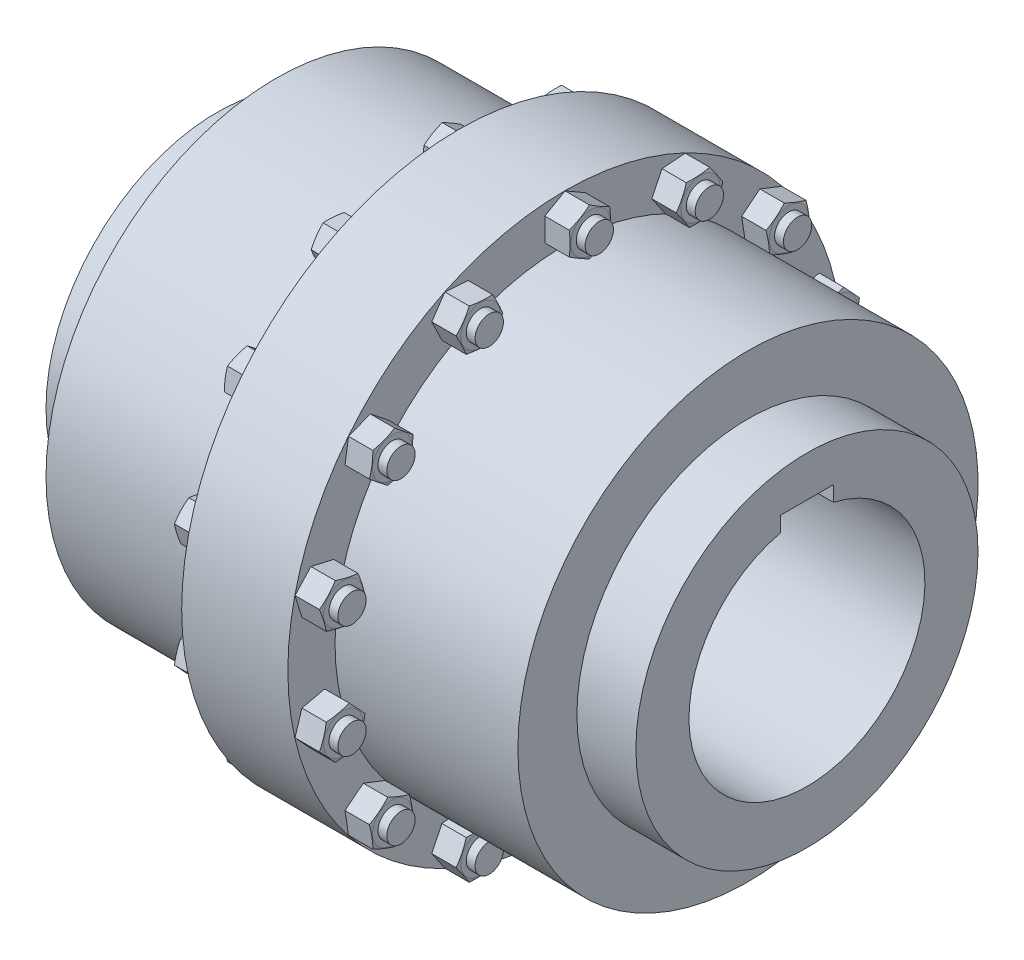
SolidWorks part; units mm, degrees
ref_plane "Спереди" through (0, 0, 0) normal (0, 0, 1) x (1, 0, 0)
ref_plane "Сверху" through (0, 0, 0) normal (0, 1, 0) x (1, 0, 0)
ref_plane "Справа" through (0, 0, 0) normal (1, 0, 0) x (0, 0, -1)
sketch "Эскиз1" plane through (0, 0, 0) normal (0, 0, 1) x (1, 0, 0)
  line L0 (-250, 100) -> (-250, 145)
  line L1 (-250, 145) -> (-200, 145)
  line L2 (-200, 145) -> (-200, 195)
  line L3 (-200, 195) -> (-45, 195)
  line L4 (200, 195) -> (200, 145)
  line L5 (45, 235) -> (45, 195)
  line L6 (45, 235) -> (-45, 235)
  line L7 (-45, 235) -> (-45, 195)
  line L8 (45, 195) -> (200, 195)
  line L9 (200, 145) -> (250, 145)
  line L10 (250, 145) -> (250, 100)
  line L12 (-10, 145) -> (-10, 100)
  line L15 (10, 145) -> (10, 100)
  line L16 (-250, 100) -> (-10, 100)
  line L18 (-98.6071, 0) -> (92.8961, 0) construction
  line L25 (10, 100) -> (250, 100)
  line L31 (0, 235) -> (0, -98.3961) construction
  line L34 (-10, 145) -> (-105, 145)
  line L35 (-105, 145) -> (-105, 172.5)
  line L36 (-105, 172.5) -> (105, 172.5)
  line L37 (105, 172.5) -> (105, 145)
  line L38 (-10, 100) -> (0, 100) construction
  line L39 (0, 100) -> (10, 100) construction
  line L40 (105, 145) -> (10, 145)
  line L41 (-199, 172.5) -> (-199, 145)
  line L42 (-199, 145) -> (-145, 145)
  line L45 (145, 172.5) -> (199, 172.5)
  line L46 (199, 172.5) -> (199, 145)
  line L47 (199, 145) -> (145, 145)
  line L48 (145, 145) -> (145, 172.5)
  line L49 (-199, 172.5) -> (-145, 172.5)
  line L50 (-199, 172.5) -> (-200, 172.5) construction
  line L51 (105, 172.5) -> (145, 172.5) construction
  line L52 (199, 172.5) -> (200, 172.5) construction
  line L53 (-145, 172.5) -> (-145, 145)
  line L54 (-105, 172.5) -> (-145, 172.5) construction
  line L55 (-199, 172.5) -> (-199, 195) construction
  line L56 (199, 195) -> (199, 172.5) construction
  point P27 (-125, 172.5)
  point P32 (125, 172.5)
  dimension "D" = 470
  dimension "dmin" = 200
  dimension "D2" = 290
  dimension "D1" = 390
  dimension "lmin" = 240
  dimension "B" = 90
  dimension "L" = 500
  dimension "bmin" = 40
  dimension "A" = 250
  dimension "lminPol" = 400
  dimension "TolKr" = 1
  dimension "TM" = 22.5
revolve "Повернуть1" add sketch "Эскиз1" angle 360 about L18
sketch "Эскиз3" plane through (0, 0, 0) normal (1, 0, 0) x (0, 0, -1)
  line L1 (-22.5, 0) -> (22.5, 0)
  line L2 (-22.5, 0) -> (-22.5, 110.4)
  line L3 (-22.5, 110.4) -> (22.5, 110.4)
  line L4 (22.5, 0) -> (22.5, 110.4)
  point P4 (0, 0)
  dimension "Bshpon" = 45
  dimension "Dplust2shpon" = 110.4
extrude "Вырез-Вытянуть1" cut sketch "Эскиз3" against normal through all both and the other way through all
sketch "Эскиз2" plane through (0, 0, 0) normal (0, 0, 1) x (1, 0, 0)
  line L0 (-60, 215) -> (74, 215)
  line L1 (66.5, 227) -> (66.5, 231.6)
  line L2 (65.6426, 234.8) -> (45, 234.8)
  line L3 (45, -235) -> (45, 235) construction
  line L4 (45, 234.8) -> (45, 227)
  line L6 (-45, 235) -> (-45, -235) construction
  line L7 (-60, 229.4) -> (-60, 215)
  line L8 (-45, 232.9) -> (-45, 227)
  line L9 (-45, 227) -> (45, 227)
  line L10 (-60, 215) -> (48.3147, 215) construction
  line L11 (-59.0622, 232.9) -> (-45, 232.9)
  line L12 (66.5, 227) -> (74, 227)
  line L13 (74, 227) -> (74, 215)
  line L15 (0, 0) -> (45.6917, 0) construction
  line L16 (-59.0622, 232.9) -> (-60, 229.4)
  line L17 (65.6426, 234.8) -> (66.5, 231.6)
  point P17 (-45, 229.95)
  dimension "d1minB" = 24
  dimension "eminG" = 39.6
  dimension "eminB" = 35.8
  dimension "lminB" = 119
  dimension "DB" = 430
  dimension "kminB" = 15
  dimension "mminG" = 21.5
  dimension "D4" = 15
  dimension "D5" = 15
  dimension "Dbolt" = 28.8
  dimension "DG" = 33.2
revolve "Повернуть2" add sketch "Эскиз2" angle 360 about L0
sketch "Эскиз5" plane through (-60, 0, 0) normal (-1, 0, 0) x (0, 0, 1)
  line L1 (0, 197.1) -> (15.5019, 206.05)
  line L2 (15.5019, 206.05) -> (15.5019, 223.95)
  line L3 (15.5019, 223.95) -> (0, 232.9)
  line L4 (0, 232.9) -> (-15.5019, 223.95)
  line L5 (-15.5019, 223.95) -> (-15.5019, 206.05)
  line L6 (-15.5019, 206.05) -> (0, 197.1)
  circle A0 centre (0, 215) radius 15.5019 construction
  circle A1 centre (0, 215) radius 17.9
  circle A2 centre (0, 215) radius 17.9 construction
extrude "Вырез-Вытянуть2" cut sketch "Эскиз5" against normal up to surface (15 mm away) contours L1 A1 | L6 A1 | L2 A1 | L3 A1 | L4 A1 | L5 A1 up to face at (-45, 215, -17.9)
sketch "Эскиз6" plane through (66.5, 0, 0) normal (1, 0, 0) x (0, 0, -1)
  line L1 (0, 195.2) -> (17.1473, 205.1)
  line L2 (17.1473, 205.1) -> (17.1473, 224.9)
  line L3 (17.1473, 224.9) -> (0, 234.8)
  line L4 (0, 234.8) -> (-17.1473, 224.9)
  line L5 (-17.1473, 224.9) -> (-17.1473, 205.1)
  line L6 (-17.1473, 205.1) -> (0, 195.2)
  circle A0 centre (0, 215) radius 17.1473 construction
  circle A1 centre (0, 215) radius 19.8
  circle A2 centre (0, 215) radius 19.8 construction
extrude "Вырез-Вытянуть3" cut sketch "Эскиз6" against normal up to surface (21.5 mm away) contours L1 A1 | L6 A1 | L2 A1 | L3 A1 | L4 A1 | L5 A1 up to face at (45, 215, 19.8)
pattern_circular "Круговой массив1" count 14 over 360 about axis through (0, 0, 0) along (1, 0, 0) of "Повернуть2", "Вырез-Вытянуть2", "Вырез-Вытянуть3"
equation "\"DB\"= ( ( \"D@Эскиз1\" - \"D1@Эскиз1\" ) / 2 ) + \"D1@Эскиз1\""
equation "\"DB@Эскиз2\"=\"DB\""
equation "\"Толщина муфты\"= ( \"D2@Эскиз1\" - \"dmin@Эскиз1\" ) / 4"
equation "\"TM@Эскиз1\"=\"Толщина муфты\""
